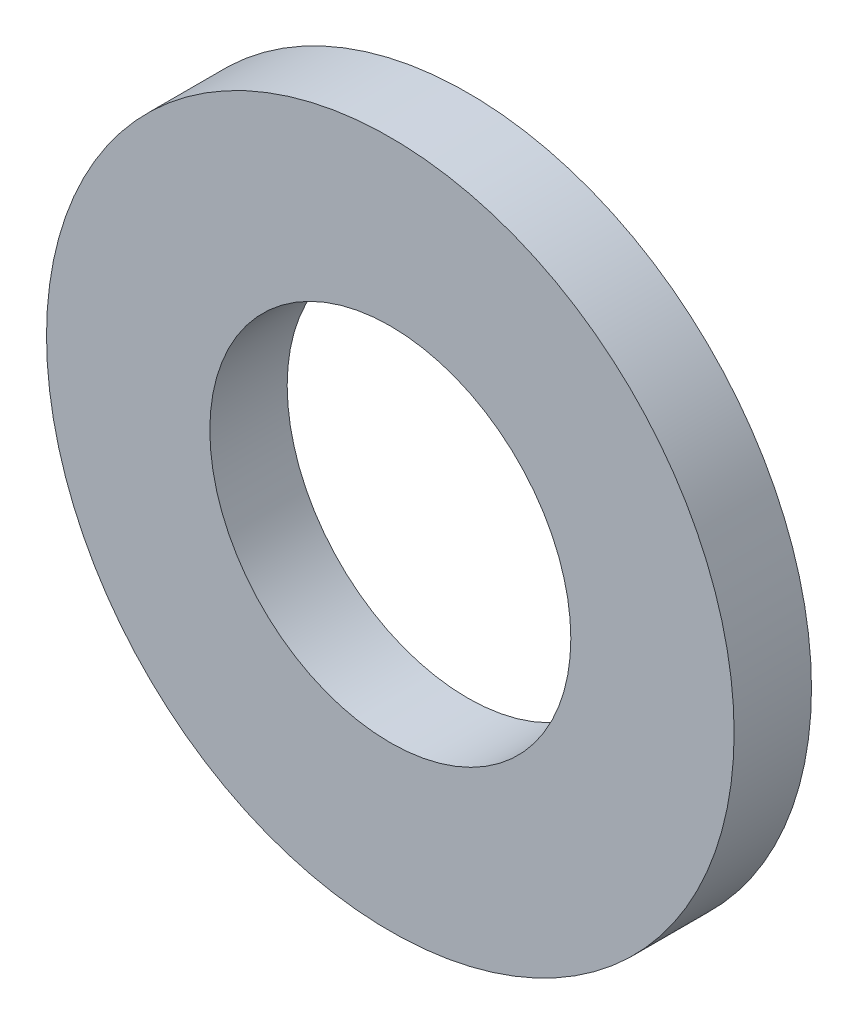
SolidWorks part; units mm, degrees
ref_plane "Front Plane" through (0, 0, 0) normal (0, 0, 1) x (1, 0, 0)
ref_plane "Top Plane" through (0, 0, 0) normal (0, 1, 0) x (1, 0, 0)
ref_plane "Right Plane" through (0, 0, 0) normal (1, 0, 0) x (0, 0, -1)
sketch "Sketch1" plane through (0, 0, 0) normal (0, 0, 1) x (1, 0, 0)
  circle A0 centre (0, 0) radius 4.2
  circle A1 centre (0, 0) radius 8
  dimension "D1" = 8.4
  dimension "D2" = 16
extrude "Boss-Extrude1" add sketch "Sketch1" along normal blind 1.8
